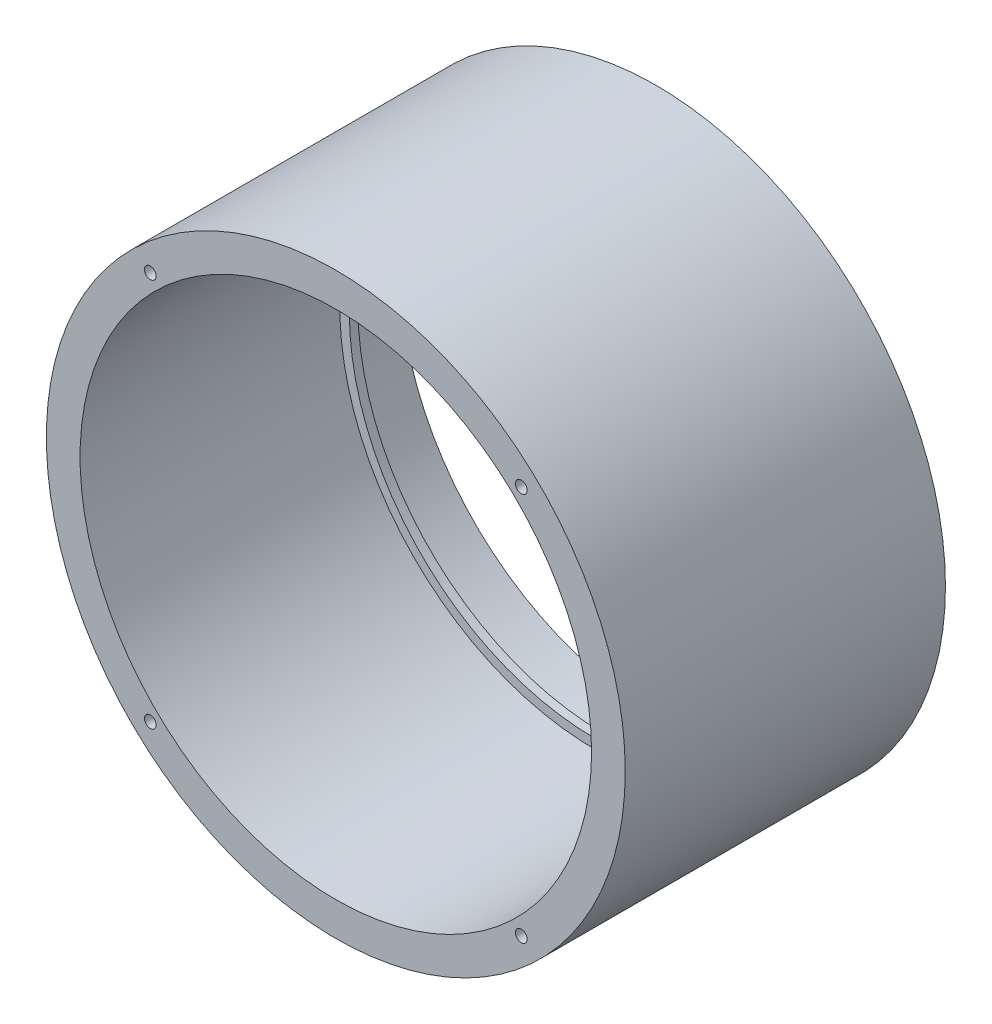
SolidWorks part; units mm, degrees
ref_plane "Front" through (0, 0, 0) normal (0, 0, 1) x (1, 0, 0)
ref_plane "Top" through (0, 0, 0) normal (0, 1, 0) x (1, 0, 0)
ref_plane "Right" through (0, 0, 0) normal (1, 0, 0) x (0, 0, -1)
sketch "Çizim1" plane through (0, 0, 0) normal (0, 0, 1) x (1, 0, 0)
  circle A0 centre (0, 0) radius 148
  circle A1 centre (0, 0) radius 167.5
  dimension "D1" = 296
  dimension "D2" = 335
extrude "Yükseklik-Ekstrüzyon2" add sketch "Çizim1" along normal blind 185.3
sketch "Çizim9" plane through (0, 0, 0) normal (0, 0, -1) x (-1, 0, 0)
  line L1 (-107.3499, 112.5) -> (107.3499, 112.5) construction
  line L2 (-107.3499, 112.5) -> (-107.3499, -112.5) construction
  line L3 (-107.3499, -112.5) -> (107.3499, -112.5) construction
  line L4 (107.3499, 112.5) -> (107.3499, -112.5) construction
  line L5 (-107.3499, 112.5) -> (107.3499, -112.5) construction
  line L6 (-107.3499, -112.5) -> (107.3499, 112.5) construction
  circle A0 centre (0, 0) radius 155.5 construction
  circle A3 centre (0, 0) radius 148 construction
  circle A4 centre (107.3499, -112.5) radius 3.4
  circle A5 centre (-107.3499, -112.5) radius 3.4
  circle A6 centre (-107.3499, 112.5) radius 3.4
  circle A7 centre (107.3499, 112.5) radius 3.4
  dimension "D1" = 7.5
  dimension "D3" = 6.8
  dimension "D2" = 225
extrude "Kes-Ekstrüzyon1" cut sketch "Çizim9" against normal blind 15
sketch "Çizim10" plane through (0, 0, 0) normal (1, 0, 0) x (0, 0, -1)
  line L0 (0, 0) -> (-115.3775, 0) construction
  line L1 (-35, 158.9078) -> (-30, 158.9078)
  line L2 (-35, 158.9078) -> (-35, 142.5)
  line L3 (-35, 142.5) -> (-30, 142.5)
  line L4 (-30, 158.9078) -> (-30, 142.5)
  line L5 (0, -167.5) -> (0, 167.5) construction
  dimension "D1" = 30
  dimension "D2" = 142.5
  dimension "D3" = 5
revolve "Döndür1" add sketch "Çizim10" angle 360 about L0
ref_plane "Düzlem1" through (0, 0, 92.65) normal (0, 0, -1) x (-1, 0, 0)
mirror "Aynalama1" about plane through (0, 0, 92.65) normal (0, 0, -1) of "Kes-Ekstrüzyon1"
